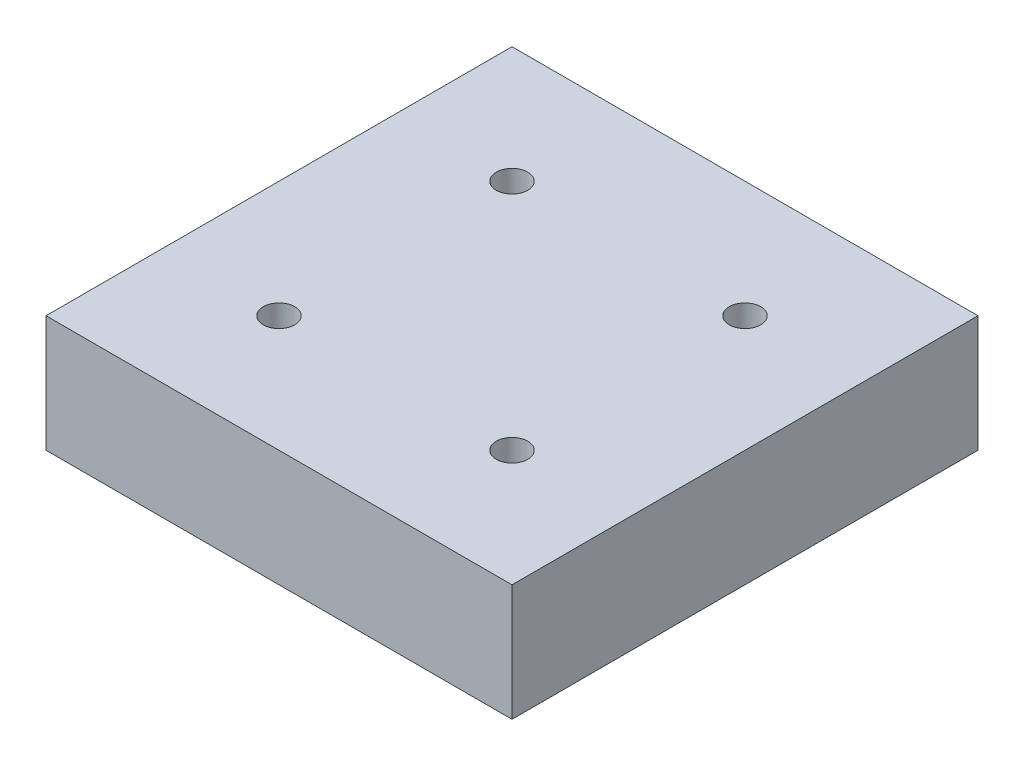
SolidWorks part; units mm, degrees
ref_plane "Alzado" through (0, 0, 0) normal (0, 0, 1) x (1, 0, 0)
ref_plane "Planta" through (0, 0, 0) normal (0, 1, 0) x (1, 0, 0)
ref_plane "Vista lateral" through (0, 0, 0) normal (1, 0, 0) x (0, 0, -1)
sketch "Croquis1" plane through (0, 0, 0) normal (0, 1, 0) x (1, 0, 0)
  line L0 (0, 8.2543) -> (0, 0) construction
  line L1 (-20, -20) -> (20, -20)
  line L2 (-20, -20) -> (-20, 20)
  line L3 (-20, 20) -> (20, 20)
  line L4 (20, -20) -> (20, 20)
  line L5 (-20, -20) -> (20, 20) construction
  line L6 (-20, 20) -> (20, -20) construction
  line L7 (0, 0) -> (10.7632, 0) construction
  circle A0 centre (-10, 10) radius 1.35
  circle A1 centre (10, 10) radius 1.35
  circle A2 centre (10, -10) radius 1.35
  circle A3 centre (-10, -10) radius 1.35
  point P0 (0, 0)
  dimension "D3" = 2.7
  dimension "D5" = 10
  dimension "D1" = 40
  dimension "D2" = 40
  dimension "D4" = 10
extrude "Saliente-Extruir1" add sketch "Croquis1" along normal blind 10
sketch "Croquis2" plane through (0, 0, -20) normal (0, 0, -1) x (-1, 0, 0)
  line L0 (0, -10) -> (17.8519, -10) construction
  line L1 (-20, 10) -> (20, 10) construction
  line L2 (9.869, 10) -> (17.8519, 10) construction
  circle A0 centre (0, 0) radius 10
  circle A1 centre (0, -6) radius 1.9
  dimension "D1" = 20
  dimension "D2" = 3.8
  dimension "D3" = 6
  dimension "D4" = 20
extrude "Saliente-Extruir2" add sketch "Croquis2" against normal blind 8
